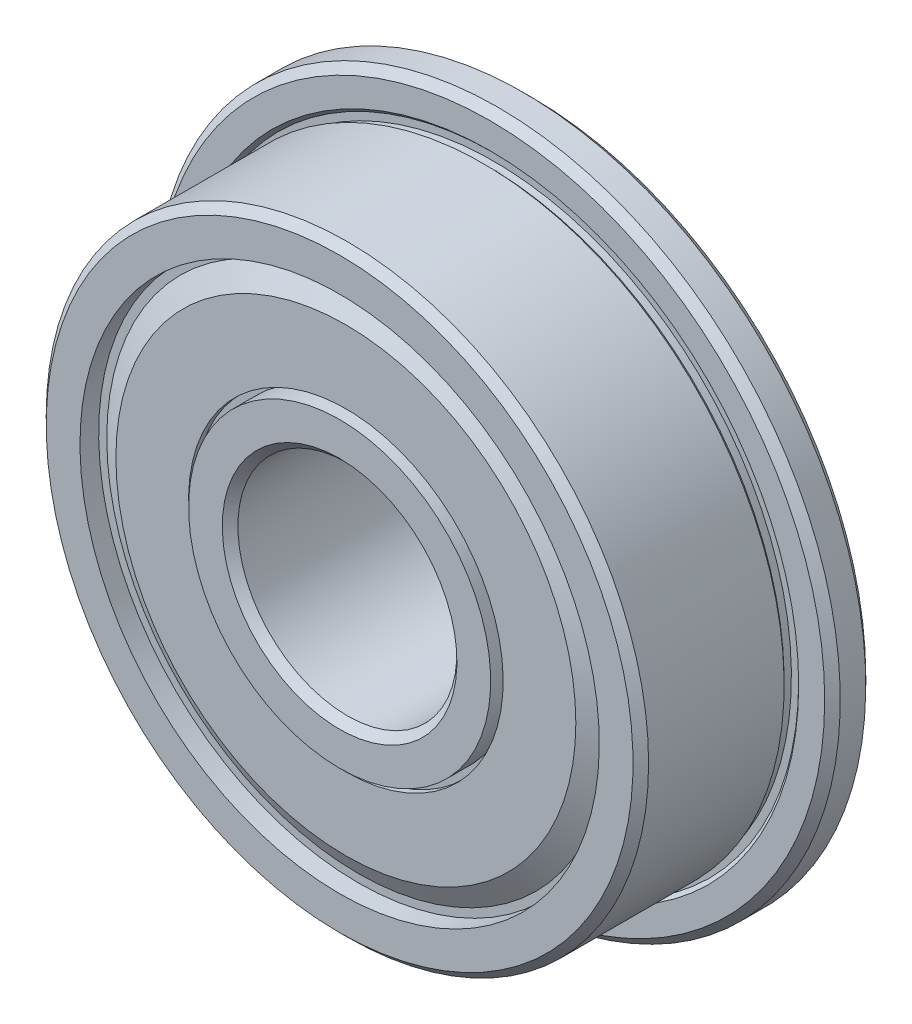
SolidWorks part; units mm, degrees
material "AISI 1045 钢，冷拔"
ref_plane "Front Plane" through (0, 0, 0) normal (0, 0, 1) x (1, 0, 0)
ref_plane "Top Plane" through (0, 0, 0) normal (0, 1, 0) x (1, 0, 0)
ref_plane "Right Plane" through (0, 0, 0) normal (1, 0, 0) x (0, 0, -1)
sketch "Sketch1" plane through (0, 0, 0) normal (1, 0, 0) x (0, 0, -1)
  line L0 (0, 11) -> (0, -11) construction
  line L1 (-3.5, 11) -> (3.5, 11) construction
  line L2 (0, 0) -> (3.5, 0) construction
  line L3 (3.5, 12.5) -> (3.5, -12.5) construction
  line L4 (3.5, -12.5) -> (2, -12.5) construction
  line L5 (3.5, 4) -> (0, 4) construction
  line L6 (3.5, 4) -> (3.5, -4) construction
  dimension "OD" = 22
  dimension "Width" = 7
  dimension "Flange Thickness" = 1.5
  dimension "ID" = 8
  dimension "Flange OD" = 25
sketch "Sketch2" plane through (0, 0, 0) normal (1, 0, 0) x (0, 0, -1)
  line L0 (3.5, 12.5) -> (2, 12.5)
  line L1 (2, 12.5) -> (2, 11.2652)
  line L2 (1.7348, 11) -> (-3.5, 11)
  line L3 (-3.5, 11) -> (-3.5, 8.725)
  line L4 (-3.5, 8.725) -> (-1.5613, 8.725)
  line L5 (3.5, 12.5) -> (3.5, -12.5) construction
  line L6 (3.5, 8.725) -> (3.5, 12.5)
  line L7 (3.5, 4) -> (-3.5, 4)
  line L8 (-3.5, 4) -> (-3.5, 6.275)
  line L9 (-3.5, 6.275) -> (-1.5613, 6.275)
  line L10 (3.5, 6.275) -> (3.5, 4)
  line L11 (0, 11) -> (0, 4) construction
  line L12 (-1.9845, 7.5) -> (1.9845, 7.5) construction
  line L13 (1.5613, 8.725) -> (3.5, 8.725)
  line L14 (1.5613, 6.275) -> (3.5, 6.275)
  line L15 (2, 11.2652) -> (2.1326, 11.1326)
  line L16 (2.1326, 11.1326) -> (2.1326, 10.8674)
  line L17 (2.1326, 10.8674) -> (1.8674, 10.8674)
  line L18 (1.8674, 10.8674) -> (1.7348, 11)
  line L19 (2, 11) -> (2.1326, 10.8674) construction
  line L20 (2.1326, 11.1326) -> (1.8674, 10.8674) construction
  line L21 (1.7348, 11) -> (2, 11) construction
  line L22 (2, 11) -> (2, 11.2652) construction
  line L23 (-3.5, 0) -> (3.5, 0) construction
  circle A0 centre (0, 7.5) radius 1.9845 construction
  arc A1 (-1.5613, 8.725) -> (1.5613, 8.725) centre (0, 7.5) cw
  arc A2 (-1.5613, 6.275) -> (1.5613, 6.275) centre (0, 7.5) ccw
  dimension "Ball Dia." = 3.969
  dimension "D2" = 135
  dimension "D3" = 0.375
  dimension "Race Thikness" = 2.275
  dimension "D4" = 2.45
revolve "Revolve1" add sketch "Sketch2" angle 360 about L2
fillet "Fillet1" radius 0.2844 3 edges at (0, -12.5, -3.5) (0, -12.5, -2) (0, -11, 3.5) profile chamfer
sketch "Sketch3" plane through (0, 0, 0) normal (0, 0, 1) x (1, 0, 0)
  line L0 (-4, 0) -> (4, 0) construction
  line L1 (-11, 0) -> (11, 0) construction
  point P5 (0, 0)
  dimension "ID2" = 8
  dimension "OD2" = 22
fillet "Fillet2" radius 0.2844 2 edges at (0, -4, -3.5) (0, -4, 3.5) profile chamfer
sketch "Sketch7" plane through (0, 0, 0) normal (0, 0, 1) x (1, 0, 0)
  line L0 (0, 9.4845) -> (0, 5.5155)
  line L1 (0, 12.5) -> (0, -12.5) construction
  line L2 (-2.6024, 9.4845) -> (0, 0) construction
  line L3 (0, 0) -> (2.6024, 9.4845) construction
  line L4 (2.6024, 9.4845) -> (-2.6024, 9.4845) construction
  circle A0 centre (0, 7.5) radius 1.9845 construction
  circle A1 centre (0, 0) radius 9.4845 construction
  circle A2 centre (0, 0) radius 5.5155 construction
  arc A4 (0, 9.4845) -> (0, 5.5155) centre (0, 7.5) ccw
  dimension "D1" = 30.686
revolve "Revolve3" add sketch "Sketch7" angle 360 about L0
pattern_circular "CirPattern3" count 8 over 360 about axis through (0, 0, 0) along (0, 0, 1) of bodies 107
sketch "Sketch8" plane through (0, 0, 0) normal (1, 0, 0) x (0, 0, -1)
  line L1 (-3.5, 8.725) -> (-2.59, 8.725)
  line L2 (-3.5, 8.725) -> (-3.5, 9.4833)
  line L3 (-3.5, 9.4833) -> (-2.59, 9.4833)
  line L4 (-2.59, 8.725) -> (-2.59, 9.4833)
  line L5 (3.5, 8.725) -> (2.59, 8.725)
  line L6 (3.5, 8.725) -> (3.5, 9.4833)
  line L7 (3.5, 9.4833) -> (2.59, 9.4833)
  line L8 (2.59, 8.725) -> (2.59, 9.4833)
  line L9 (3.5, 6.275) -> (2.59, 6.275)
  line L10 (3.5, 6.275) -> (3.5, 5.5167)
  line L11 (3.5, 5.5167) -> (2.59, 5.5167)
  line L12 (2.59, 6.275) -> (2.59, 5.5167)
  line L13 (-3.5, 6.275) -> (-2.59, 6.275)
  line L14 (-3.5, 6.275) -> (-3.5, 5.5167)
  line L15 (-3.5, 5.5167) -> (-2.59, 5.5167)
  line L16 (-2.59, 6.275) -> (-2.59, 5.5167)
  dimension "D1" = 0.7583
  dimension "D2" = 0.91
revolve "Cut-Revolve1" cut sketch "Sketch8" angle 360 about L2
sketch "Sketch9" plane through (0, 0, 0) normal (1, 0, 0) x (0, 0, -1)
  line L0 (-2.59, 9.4833) -> (-2.59, 9.1262)
  line L1 (-2.59, 9.1262) -> (-3.045, 8.3381)
  line L2 (-3.045, 8.3381) -> (-3.045, 5.7442)
  line L3 (3.045, 5.7442) -> (3.045, 5.5167) construction
  line L4 (2.59, 9.4833) -> (2.59, 9.1262)
  line L5 (2.59, 9.1262) -> (3.045, 8.3381)
  line L6 (3.045, 8.3381) -> (3.045, 5.7442)
  line L7 (3.5, 5.5167) -> (2.59, 5.5167) construction
  line L8 (-2.8175, 9.4833) -> (-2.8175, 9.1871)
  line L9 (-2.8175, 9.1871) -> (-3.2725, 8.3991)
  line L10 (-3.2725, 8.3991) -> (-3.2725, 5.7442)
  line L11 (-2.59, 9.4833) -> (-2.8175, 9.4833)
  line L12 (-3.045, 5.7442) -> (-3.2725, 5.7442)
  line L13 (2.8175, 9.4833) -> (2.8175, 9.1871)
  line L14 (2.8175, 9.1871) -> (3.2725, 8.3991)
  line L15 (3.2725, 8.3991) -> (3.2725, 5.7442)
  line L16 (2.59, 9.4833) -> (2.8175, 9.4833)
  line L17 (3.045, 5.7442) -> (3.2725, 5.7442)
  line L18 (-2.59, 9.1262) -> (-2.59, 2.5308) construction
  line L19 (2.59, 9.1262) -> (2.59, 9.4833) construction
  line L20 (-2.59, 5.5167) -> (-3.5, 5.5167) construction
  line L22 (-3.045, 5.7442) -> (-3.045, 5.5167) construction
  dimension "D2" = 150
  dimension "D1" = 150
  dimension "D5" = 0.91
  dimension "D3" = 0.2275
  dimension "D4" = 0.2275
  dimension "D6" = 0.3571
revolve "Revolve4" add sketch "Sketch9" angle 360 about L2
equation "\"D1@Fillet1\"=\"Race Thikness@Sketch2\"/8"
equation "\"ID2@Sketch3\" = \"ID@Sketch1\""
equation "\"OD2@Sketch3\" = \"OD@Sketch1\""
equation "\"D1@Fillet2\"=\"Race Thikness@Sketch2\"/8"
equation "\"D1@CirPattern3\"=360/\"D1@Sketch7\"-4"
equation "\"D1@Sketch8\"=\"Race Thikness@Sketch2\"/3"
equation "\"D2@Sketch8\"=\"Race Thikness@Sketch2\"/2.5"
equation "\"D3@Sketch9\"=\"D5@Sketch9\"/4"
equation "\"D4@Sketch9\"=\"D5@Sketch9\"/4"
equation "\"D1@Sketch9\"=\"D2@Sketch9\""
equation "\"Ball Dia.@Sketch2\" = \"D1@Sketch2\"*.5"
equation "\"D4@Sketch2\"=((\"OD@Sketch1\"-\"ID@Sketch1\")/2)*.35"
